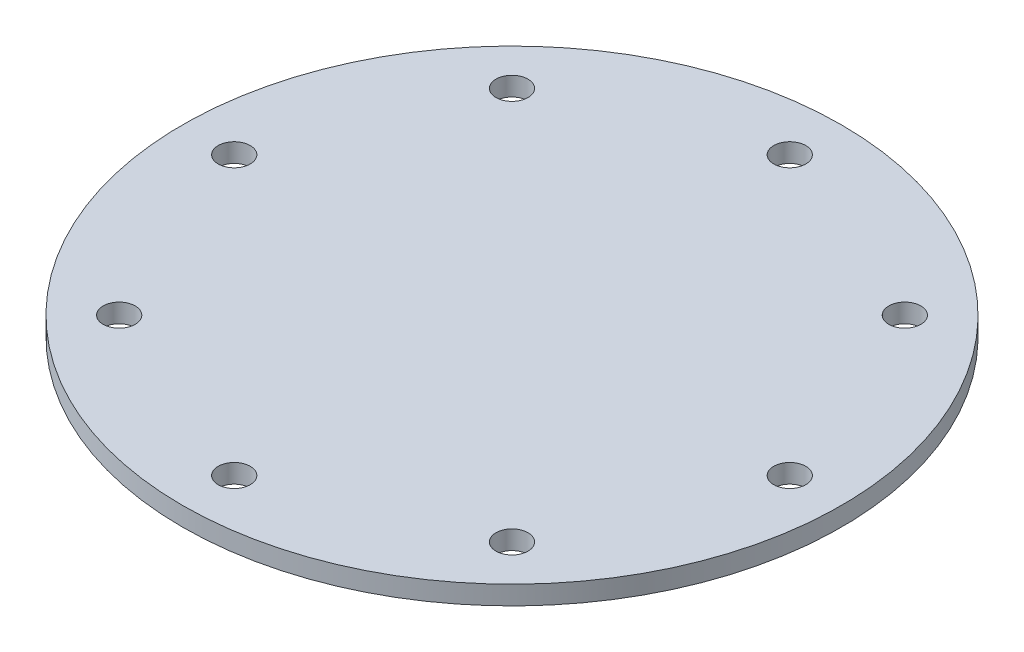
SolidWorks part; units mm, degrees
material "AISI 304"
ref_plane "Спереди" through (0, 0, 0) normal (0, 0, 1) x (1, 0, 0)
ref_plane "Сверху" through (0, 0, 0) normal (0, 1, 0) x (1, 0, 0)
ref_plane "Справа" through (0, 0, 0) normal (1, 0, 0) x (0, 0, -1)
sketch "Эскиз1" plane through (0, 0, 0) normal (0, 1, 0) x (1, 0, 0)
  line L0 (0, 0) -> (59, 0) construction
  circle A0 centre (0, 0) radius 70
  circle A1 centre (0, 0) radius 59 construction
  circle A2 centre (59, 0) radius 3.4
  circle A3 centre (41.7193, -41.7193) radius 3.4
  circle A4 centre (0, -59) radius 3.4
  circle A5 centre (-41.7193, -41.7193) radius 3.4
  circle A6 centre (-59, 0) radius 3.4
  circle A7 centre (-41.7193, 41.7193) radius 3.4
  circle A8 centre (0, 59) radius 3.4
  circle A9 centre (41.7193, 41.7193) radius 3.4
  dimension "D1" = 140
  dimension "D2" = 118
  dimension "D3" = 6.8
  dimension "D4" = 8
extrude "Бобышка-Вытянуть1" add sketch "Эскиз1" along normal blind 4
